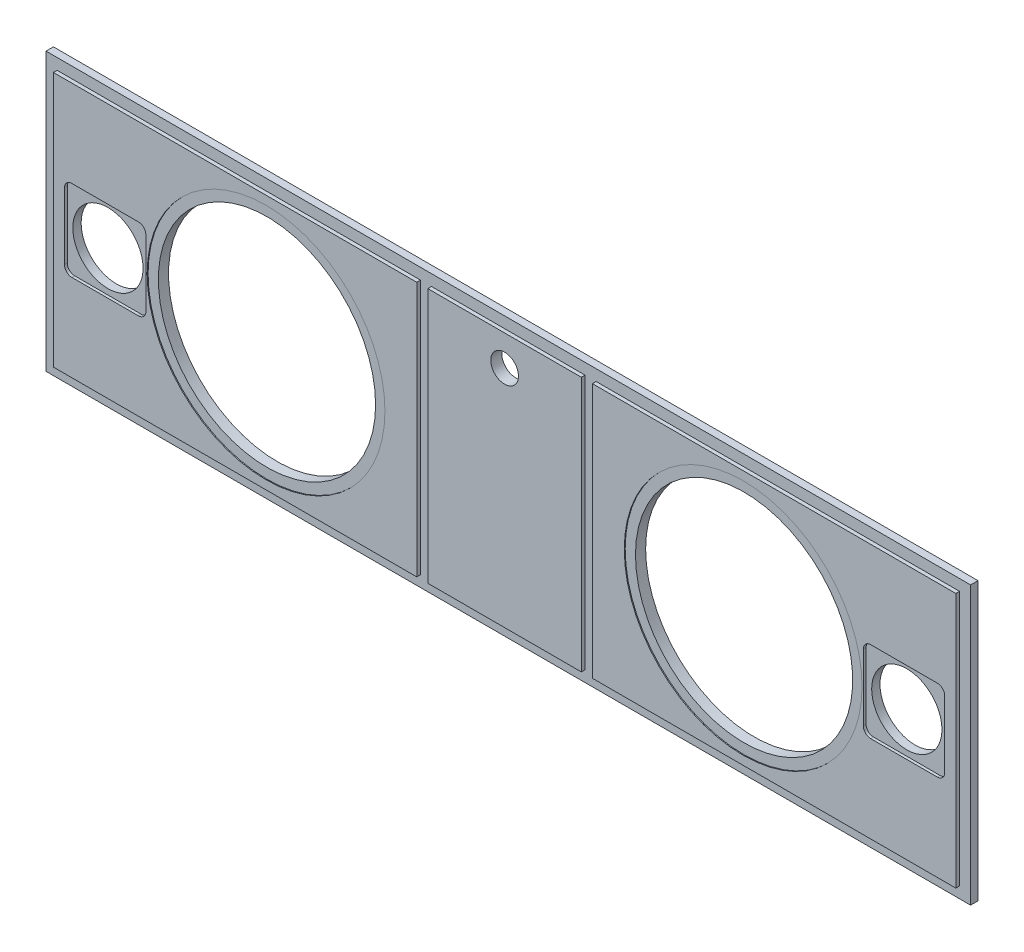
SolidWorks part; units mm, degrees
material "Pine"
ref_plane "Front Plane" through (0, 0, 0) normal (0, 0, 1) x (1, 0, 0)
ref_plane "Top Plane" through (0, 0, 0) normal (0, 1, 0) x (1, 0, 0)
ref_plane "Right Plane" through (0, 0, 0) normal (1, 0, 0) x (0, 0, -1)
sketch "Panel" plane through (0, 0, 0) normal (0, 0, 1) x (1, 0, 0)
  line L5 (500, 424.6951) -> (500, -112.2601) construction
  line L6 (0, 0) -> (1000, 0)
  line L10 (0, 0) -> (0, 300)
  line L11 (0, 300) -> (1000, 300)
  line L12 (1000, 0) -> (1000, 300)
  circle A0 centre (242, 150) radius 117.475
  circle A2 centre (758, 150) radius 117.475
  circle A3 centre (68, 150) radius 38
  circle A4 centre (932, 150) radius 38
  dimension "D8" = 76
  dimension "D1" = 234.95
  dimension "D10" = 234.95
  dimension "D2" = 1000
  dimension "D4" = 242
  dimension "D6" = 68
  dimension "D9" = 242
  dimension "D3" = 300
  dimension "D7" = 150
  dimension "D5" = 150
extrude "Panel Ply" add sketch "Panel" along normal blind 12 contours A2
sketch "Sketch4" plane through (0, 0, 12) normal (0, 0, 1) x (1, 0, 0)
  line L0 (0, 0) -> (0, 300) construction
  line L1 (32, 194) -> (104, 194)
  line L2 (24, 186) -> (24, 114)
  line L3 (32, 106) -> (104, 106)
  line L4 (112, 186) -> (112, 114)
  line L5 (0, 0) -> (0, 300) construction
  line L6 (0, 300) -> (1000, 300) construction
  line L7 (500, -84.0445) -> (500, 394.2312) construction
  line L8 (968, 106) -> (896, 106)
  line L9 (888, 186) -> (888, 114)
  line L10 (968, 194) -> (896, 194)
  line L11 (976, 186) -> (976, 114)
  arc A0 (104, 194) -> (112, 186) centre (104, 186) cw
  arc A1 (104, 106) -> (112, 114) centre (104, 114) ccw
  arc A2 (24, 114) -> (32, 106) centre (32, 114) ccw
  arc A3 (24, 186) -> (32, 194) centre (32, 186) cw
  arc A4 (896, 106) -> (888, 114) centre (896, 114) cw
  arc A5 (896, 194) -> (888, 186) centre (896, 186) ccw
  arc A6 (976, 114) -> (968, 106) centre (968, 114) cw
  arc A7 (976, 186) -> (968, 194) centre (968, 186) ccw
  point P16 (67.7235, 149.5451)
  dimension "D1" = 8
  dimension "D2" = 88
  dimension "D3" = 88
  dimension "D4" = 24
  dimension "D5" = 106
  dimension "D6" = 500
extrude "Pizeo Pocket Cut" cut sketch "Sketch4" against normal blind 3 contours L2 A2 L3 A1 L4 A0 L1 A3 | L8 A4 L9 A5 L10 A7 L11 A6
sketch "Sketch6" plane through (0, 0, 12) normal (0, 0, 1) x (1, 0, 0)
  line L2 (0, 300) -> (1000, 300) construction
  line L3 (500, 300) -> (500, 241.385) construction
  circle A0 centre (500, 255) radius 15
  dimension "D3" = 30
  dimension "D2" = 45
extrude "Cord Cut" cut sketch "Sketch6" against normal up to surface (12 mm away) up to face at (894, 150, 0)
sketch "Sketch7" plane through (0, 0, 12) normal (0, 0, 1) x (1, 0, 0)
  line L0 (1000, 0) -> (1000, 300) construction
  line L1 (0, 300) -> (1000, 300)
  line L2 (0, 300) -> (0, 288)
  line L3 (0, 288) -> (1000, 288)
  line L4 (1000, 300) -> (1000, 288)
  line L6 (0, 0) -> (1000, 0)
  line L7 (0, 0) -> (0, 12)
  line L8 (0, 12) -> (1000, 12)
  line L9 (1000, 0) -> (1000, 12)
  dimension "D1" = 12
  dimension "D2" = 12
extrude "Horizontal Housing Cut" cut sketch "Sketch7" against normal blind 4
sketch "Sketch8" plane through (0, 0, 12) normal (0, 0, 1) x (1, 0, 0)
  line L0 (1000, 12) -> (0, 12) construction
  line L1 (0, 288) -> (12, 288)
  line L2 (0, 288) -> (0, 12)
  line L3 (0, 12) -> (12, 12)
  line L4 (12, 288) -> (12, 12)
  line L5 (1000, 12) -> (0, 12) construction
  line L6 (1000, 288) -> (988, 288)
  line L7 (1000, 288) -> (1000, 12)
  line L8 (1000, 12) -> (988, 12)
  line L9 (988, 288) -> (988, 12)
  line L10 (0, 288) -> (1000, 288) construction
  line L11 (405, 288) -> (417, 288)
  line L12 (405, 288) -> (405, 12)
  line L13 (405, 12) -> (417, 12)
  line L14 (417, 288) -> (417, 12)
  line L16 (583, 288) -> (595, 288)
  line L17 (583, 288) -> (583, 12)
  line L18 (583, 12) -> (595, 12)
  line L19 (595, 288) -> (595, 12)
  dimension "D1" = 12
  dimension "D2" = 12
  dimension "D3" = 12
  dimension "D4" = 12
  dimension "D5" = 393
  dimension "D6" = 393
extrude "Vertical Housing Cut" cut sketch "Sketch8" against normal blind 4
sketch "Sketch9" plane through (0, 0, 12) normal (0, 0, 1) x (1, 0, 0)
  line L0 (500, 300) -> (500, 0) construction
  line L1 (1000, 300) -> (0, 300) construction
  line L2 (0, 0) -> (1000, 0) construction
  circle A0 centre (242, 150) radius 128.5875
  circle A1 centre (758, 150) radius 128.5875
  dimension "D1" = 257.175
extrude "Cut-Extrude1" cut sketch "Sketch9" against normal blind 1
equation "\"LENGTH\" = 1000mm"
equation "\"D2@Panel\" = \"LENGTH\""
equation "\"D6@Sketch4\"=\"LENGTH\"/2"
equation "\"PLY\"= 12mm"
equation "\"D1@Panel Ply\" = \"PLY\""
equation "\"WIDTH\" = 300mm"
equation "\"CENTER_BRACE_LENGTH\" = 393mm"
equation "\"PANEL_WIDTH\"= \"LENGTH\" - \"CENTER_BRACE_LENGTH\" * 2 - \"PLY\" * 4"
equation "\"PANEL_SMALL_HEIGHT\" = 70mm"
equation "\"D2@Sketch7\"=\"PLY\""
equation "\"D1@Sketch7\"=\"PLY\""
equation "\"HEIGHT\" = 300mm"
equation "\"HOUSING_DEPTH\" = 4mm"
equation "\"PORT_WIDTH\" = 90mm"
equation "\"PORT_RADIUS\" = 15mm"
equation "\"PORT_BRACE_HEIGHT\" = 92mm"
equation "\"DOWEL_SIZE\" = 0.25in"
equation "\"DOWEL_OFFSET\" = 30mm"
equation "\"D1@Horizontal Housing Cut\" = \"HOUSING_DEPTH\""
equation "\"D3@Panel\" = \"HEIGHT\""
equation "\"D7@Panel\" = \"HEIGHT\" / 2"
equation "\"D5@Panel\" = \"HEIGHT\" / 2"
equation "\"D1@Sketch8\"=\"PLY\""
equation "\"D2@Sketch8\"=\"PLY\""
equation "\"D1@Vertical Housing Cut\" = \"HOUSING_DEPTH\""
equation "\"D3@Sketch8\"=\"PLY\""
equation "\"D4@Sketch8\"=\"PLY\""
equation "\"D5@Sketch8\"=\"CENTER_BRACE_LENGTH\""
equation "\"D1@Sketch9\"=\"GW1058_outside_diameter\""
equation "\"GW1058_outside_diameter\" = 10.125in"
equation "\"GW1058_baffle_cutout_diameter\" = 9.25in"
equation "\"D1@Panel\"=\"GW1058_baffle_cutout_diameter\""
